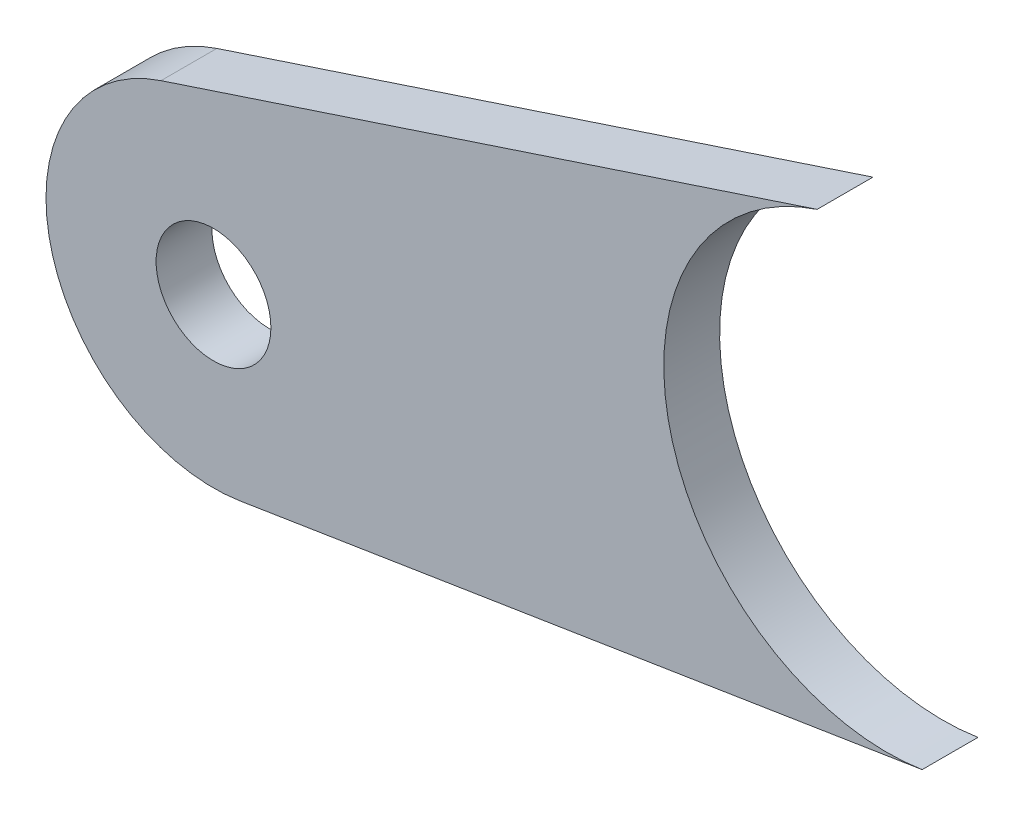
SolidWorks part; units mm, degrees
ref_plane "Front Plane" through (0, 0, 0) normal (0, 0, 1) x (1, 0, 0)
ref_plane "Top Plane" through (0, 0, 0) normal (0, 1, 0) x (1, 0, 0)
ref_plane "Right Plane" through (0, 0, 0) normal (1, 0, 0) x (0, 0, -1)
sketch "Sketch1" plane through (0, 0, 0) normal (0, 0, 1) x (1, 0, 0)
  line L0 (103.059, -9.407) -> (141.8616, -3.2422)
  line L1 (103.059, -9.407) -> (141.8616, -3.2422)
  line L2 (145.1957, 11.1463) -> (97.75, -5.295) construction
  line L3 (145.1957, 11.1463) -> (97.75, -5.295) construction
  line L5 (98.5788, 9.045) -> (135.888, 21.3604)
  line L8 (101.5644, 0) -> (139.8689, 9.3004)
  circle A0 centre (101.5644, 0) radius 9.525
  circle A1 centre (139.8689, 9.3004) radius 12.7
  circle A2 centre (101.5644, 0) radius 3.2639
  point P7 (139.9532, 9.045)
  dimension "D1" = 19.05
  dimension "D2" = 25.4
  dimension "D3" = 6.5278
extrude "Boss-Extrude1" add sketch "Sketch1" along normal blind 3.175
